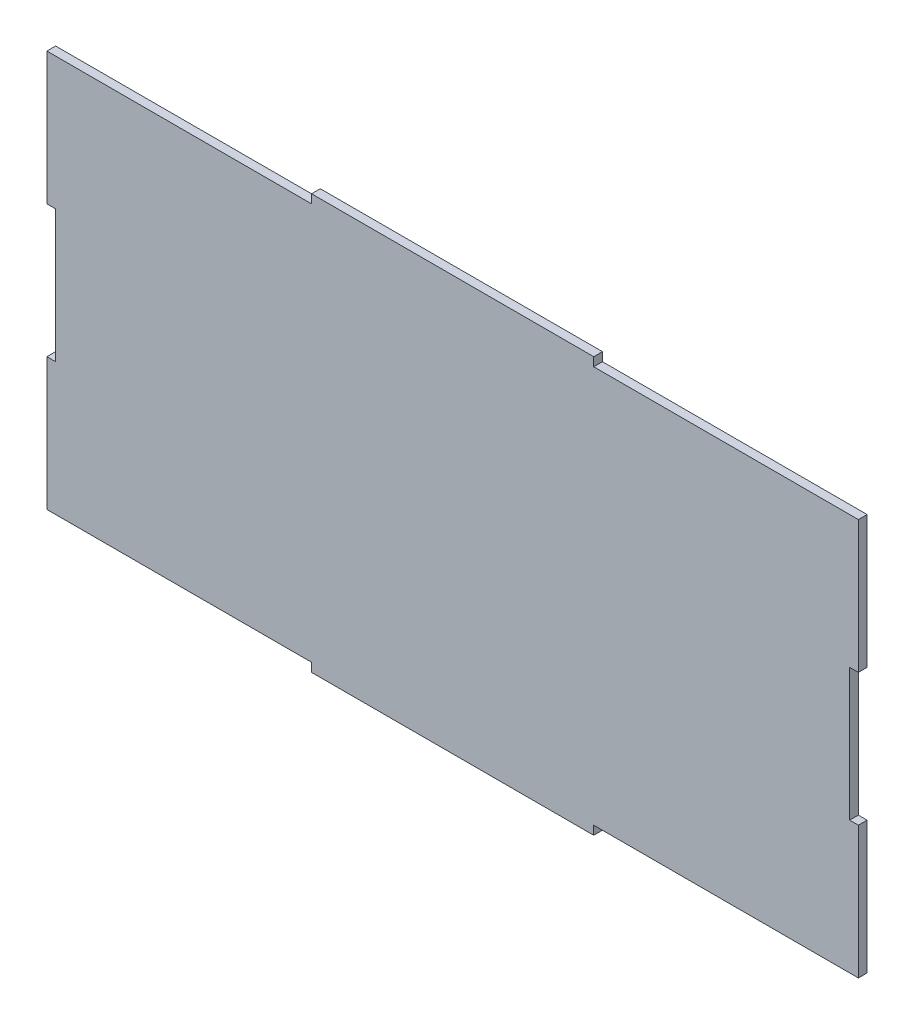
SolidWorks part; units mm, degrees
ref_plane "Alzado" through (0, 0, 0) normal (0, 0, 1) x (1, 0, 0)
ref_plane "Planta" through (0, 0, 0) normal (0, 1, 0) x (1, 0, 0)
ref_plane "Vista lateral" through (0, 0, 0) normal (1, 0, 0) x (0, 0, -1)
sketch "Croquis1" plane through (0, 0, 0) normal (0, 0, 1) x (1, 0, 0)
  line L0 (-153.3, -25) -> (-153.3, -75)
  line L1 (-153.3, 75) -> (-53.3, 75)
  line L2 (-153.3, 75) -> (-153.3, 25)
  line L3 (-153.3, -75) -> (-53.3, -75)
  line L4 (153.3, 75) -> (153.3, 25)
  line L6 (-53.3, 75) -> (-53.3, 78.3)
  line L7 (-53.3, 78.3) -> (53.3, 78.3)
  line L8 (53.3, 75) -> (53.3, 78.3)
  line L9 (153.3, 25) -> (150, 25)
  line L11 (153.3, -25) -> (150, -25)
  line L12 (150, 25) -> (150, -25)
  line L14 (53.3, -75) -> (53.3, -78.3)
  line L15 (53.3, -78.3) -> (-53.3, -78.3)
  line L16 (-53.3, -75) -> (-53.3, -78.3)
  line L17 (-153.3, -25) -> (-150, -25)
  line L20 (-150, -25) -> (-150, 25)
  line L21 (53.3, 75) -> (153.3, 75)
  line L22 (153.3, -25) -> (153.3, -75)
  line L23 (53.3, -75) -> (153.3, -75)
  line L24 (-153.3, 25) -> (-150, 25)
  point P20 (150, 0)
  point P21 (0, 78.3)
  dimension "D1" = 3.3
  dimension "D2" = 150
  dimension "D3" = 306.6
  dimension "D4" = 100
  dimension "D5" = 100
extrude "Saliente-Extruir1" add sketch "Croquis1" along normal blind 3.3
